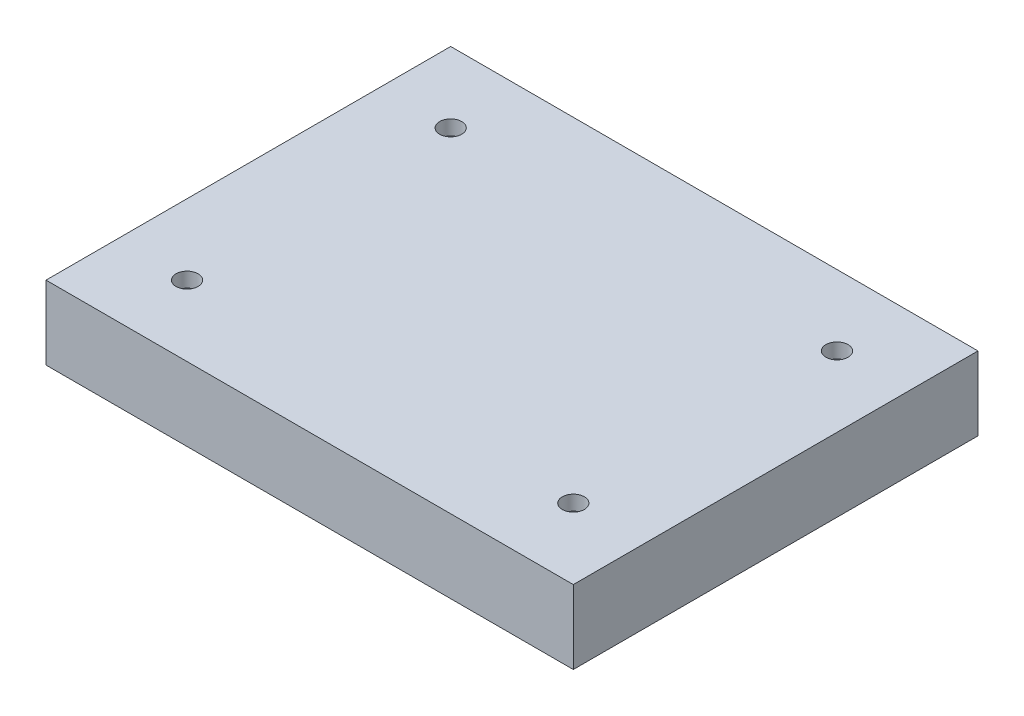
SolidWorks part; units mm, degrees
ref_plane "Front Plane" through (0, 0, 0) normal (0, 0, 1) x (1, 0, 0)
ref_plane "Top Plane" through (0, 0, 0) normal (0, 1, 0) x (1, 0, 0)
ref_plane "Right Plane" through (0, 0, 0) normal (1, 0, 0) x (0, 0, -1)
sketch "Sketch1" plane through (0, 0, 0) normal (0, 1, 0) x (1, 0, 0)
  line L1 (-43, -33) -> (43, -33)
  line L2 (-43, -33) -> (-43, 33)
  line L3 (-43, 33) -> (43, 33)
  line L4 (43, -33) -> (43, 33)
  line L5 (-43, -33) -> (43, 33) construction
  line L6 (-43, 33) -> (43, -33) construction
  point P0 (0, 0)
extrude "Boss-Extrude1" add sketch "Sketch1" along normal blind 12
sketch "Sketch2" plane through (0, 0, 0) normal (0, -1, 0) x (1, 0, 0)
  line L1 (-40.6, -30.6) -> (40.6, -30.6)
  line L2 (-40.6, -30.6) -> (-40.6, 30.6)
  line L3 (-40.6, 30.6) -> (40.6, 30.6)
  line L4 (40.6, -30.6) -> (40.6, 30.6)
  line L5 (-40.6, -30.6) -> (40.6, 30.6) construction
  line L6 (-40.6, 30.6) -> (40.6, -30.6) construction
  point P0 (0, 0)
extrude "Cut-Extrude1" cut sketch "Sketch2" against normal blind 9.6
sketch "Sketch3" plane through (0, 9.6, 0) normal (0, -1, 0) x (1, 0, 0)
  circle A0 centre (-31.5, -21.5) radius 3
  circle A1 centre (31.5, -21.5) radius 3
  circle A2 centre (-31.5, 21.5) radius 3
  circle A3 centre (31.5, 21.5) radius 3
extrude "Boss-Extrude2" add sketch "Sketch3" along normal blind 4.5
sketch "Sketch4" plane through (0, 9.6, 0) normal (0, -1, 0) x (1, 0, 0)
  circle A0 centre (-31.5, -21.5) radius 1.8
  circle A1 centre (31.5, -21.5) radius 1.8
  circle A2 centre (-31.5, 21.5) radius 1.8
  circle A3 centre (31.5, 21.5) radius 1.8
extrude "Cut-Extrude2" cut sketch "Sketch4" against normal blind 4.5
